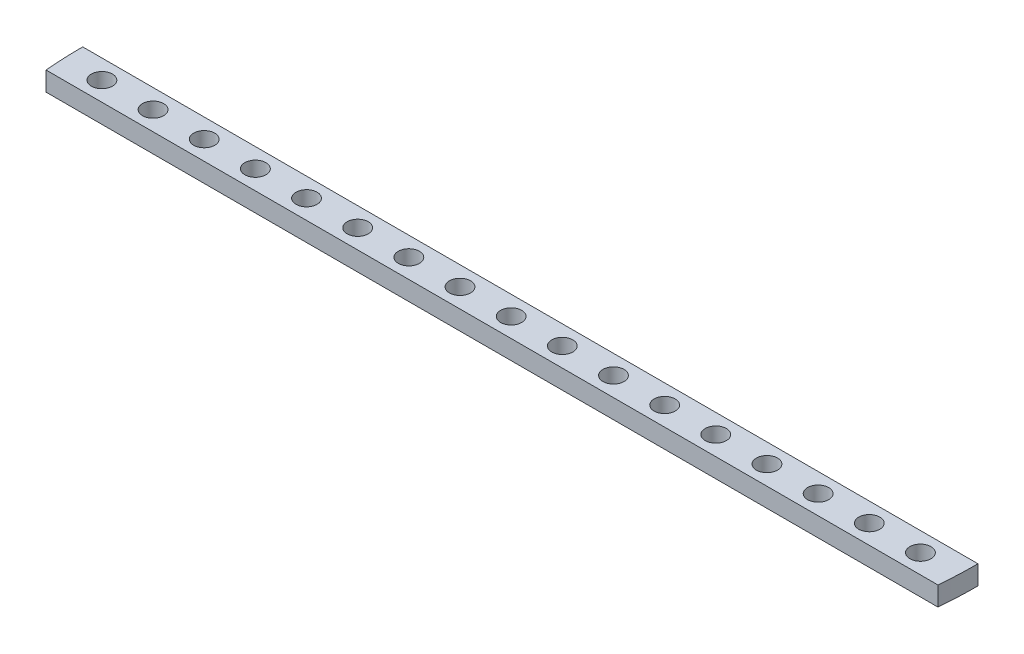
SolidWorks part; units mm, degrees
ref_plane "前视基准面" through (0, 0, 0) normal (0, 0, 1) x (1, 0, 0)
ref_plane "上视基准面" through (0, 0, 0) normal (0, 1, 0) x (1, 0, 0)
ref_plane "右视基准面" through (0, 0, 0) normal (1, 0, 0) x (0, 0, -1)
sketch "草图1" plane through (0, 0, 0) normal (0, 1, 0) x (1, 0, 0)
  line L0 (-50, 0) -> (50, 0)
  arc A0 (50, 0) -> (-50, 0) centre (0, 0) cw
extrude "凸台-拉伸1" add sketch "草图1" along normal blind 4
sketch "草图2" plane through (0, 4, 0) normal (0, 1, 0) x (1, 0, 0)
  line L2 (0, -10.623) -> (10, -10.623)
  line L3 (10, -10.623) -> (10, -30.623)
  line L4 (10, -30.623) -> (-30, -30.623)
  line L5 (-30, -30.623) -> (-30, -10.623)
  line L6 (-30, -10.623) -> (0, -10.623)
extrude "切除-拉伸1" cut sketch "草图2" against normal blind 10
sketch "草图3" plane through (0, 4, 0) normal (0, 1, 0) x (1, 0, 0)
  circle A0 centre (-34.75, -15.623) radius 2.25
  circle A1 centre (-34.75, -25.623) radius 2.25
  circle A2 centre (14.75, -25.623) radius 2.25
  circle A3 centre (14.75, -15.623) radius 2.25
extrude "切除-拉伸2" cut sketch "草图3" against normal blind 10
sketch "草图4" plane through (0, 4, 0) normal (0, 1, 0) x (1, 0, 0)
  circle A0 centre (0, -3) radius 1.65
  circle A1 centre (8, -3) radius 1.65
  circle A2 centre (16, -3) radius 1.65
  circle A3 centre (24, -3) radius 1.65
  circle A4 centre (32, -3) radius 1.65
  circle A5 centre (40, -3) radius 1.65
  circle A6 centre (-40, -3) radius 1.65
  circle A7 centre (-32, -3) radius 1.65
  circle A8 centre (-24, -3) radius 1.65
  circle A9 centre (-16, -3) radius 1.65
  circle A10 centre (-8, -3) radius 1.65
extrude "切除-拉伸3" cut sketch "草图4" against normal blind 10
sketch "草图5" plane through (0, 4, 0) normal (0, 1, 0) x (1, 0, 0)
  line L0 (-70, 0) -> (70, 0)
  circle A0 centre (0, 0) radius 70
  circle A1 centre (0, 0) radius 50
  arc M20 (-50, 0) -> (50, 0) centre (0, 0) ccw
extrude "凸台-拉伸2" add sketch "草图5" against normal blind 4 contours L0 A0 M20
sketch "草图6" plane through (0, 4, 0) normal (0, 1, 0) x (1, 0, 0)
  circle A0 centre (0, -3) radius 1.65
  circle A1 centre (8, -3) radius 1.65
  circle A2 centre (16, -3) radius 1.65
  circle A3 centre (24, -3) radius 1.65
  circle A4 centre (32, -3) radius 1.65
  circle A5 centre (40, -3) radius 1.65
  circle A6 centre (48, -3) radius 1.65
  circle A7 centre (56, -3) radius 1.65
  circle A8 centre (64, -3) radius 1.65
  circle A9 centre (-8, -3) radius 1.65
  circle A10 centre (-16, -3) radius 1.65
  circle A11 centre (-24, -3) radius 1.65
  circle A12 centre (-32, -3) radius 1.65
  circle A13 centre (-40, -3) radius 1.65
  circle A14 centre (-48, -3) radius 1.65
  circle A15 centre (-56, -3) radius 1.65
  circle A16 centre (-64, -3) radius 1.65
  dimension "D1" = 9
  dimension "D2" = 8
extrude "切除-拉伸4" cut sketch "草图6" against normal blind 4
sketch "草图7" plane through (0, 4, 0) normal (0, 1, 0) x (1, 0, 0)
  line L1 (-30, -20.623) -> (-30, -30.623)
  line L2 (10, -20.623) -> (10, -30.623)
  line L3 (-30, -30.623) -> (10, -30.623)
  line L4 (-30, -10.623) -> (-30, -30.623) construction
  line L5 (10, -30.623) -> (10, -10.623) construction
  line L7 (-30, -20.623) -> (10, -20.623)
  line L8 (-30, -20.623) -> (-30, -40.623)
  line L9 (10, -20.623) -> (10, -40.623)
  line L10 (-30, -40.623) -> (10, -40.623)
  line L11 (-34.75, -15.623) -> (14.75, -15.623)
  line L12 (14.75, -15.623) -> (14.75, -25.623)
  line L13 (14.75, -25.623) -> (14.75, -35.623)
  line L14 (-34.75, -15.623) -> (-34.75, -25.623)
  line L15 (-34.75, -25.623) -> (-34.75, -35.623)
  circle A1 centre (-34.75, -35.623) radius 2.25
  circle A2 centre (14.75, -35.623) radius 2.25
extrude "切除-拉伸5" cut sketch "草图7" against normal blind 4
sketch "草图8" plane through (0, 4, 0) normal (0, 1, 0) x (1, 0, 0)
  line L0 (-34.75, -15.623) -> (14.75, -15.623)
  line L1 (14.75, -15.623) -> (14.75, -25.623)
  line L2 (14.75, -25.623) -> (14.75, -20.623)
  line L3 (14.75, -20.623) -> (-41.5549, -20.623)
  line L4 (-41.5549, -20.623) -> (-41.5549, -8.5064)
  line L5 (-41.5549, -8.5064) -> (21.0409, -8.9873)
  line L6 (21.0409, -8.9873) -> (21.0409, -20.623)
  line L7 (21.0409, -20.623) -> (14.75, -20.623)
extrude "凸台-拉伸4" add sketch "草图8" against normal blind 4
sketch "草图9" plane through (0, 4, 0) normal (0, 1, 0) x (1, 0, 0)
  line L0 (0, -70) -> (0, -80)
  line L1 (0, -80) -> (-10, -80)
  line L2 (-10, -80) -> (10, -80)
  line L3 (80, -80) -> (77, -80)
  line L4 (80, -10) -> (80, -150)
  line L5 (-30, -20.623) -> (10, -20.623)
  line L6 (-30, -20.623) -> (-30, -40.623)
  line L7 (10, -20.623) -> (10, -40.623)
  line L8 (-30, -40.623) -> (10, -40.623)
  line L9 (59.377, -90) -> (39.377, -90)
  line L10 (59.377, -50) -> (59.377, -90)
  line L11 (59.377, -50) -> (39.377, -50)
  line L12 (39.377, -50) -> (39.377, -90)
  line L17 (-59.377, -70) -> (-39.377, -70)
  line L18 (-59.377, -110) -> (-59.377, -70)
  line L19 (-59.377, -110) -> (-39.377, -110)
  line L20 (-39.377, -110) -> (-39.377, -70)
  line L21 (-80, -10) -> (-80, -150)
  arc A1 (80, -10) -> (80, -150) centre (80, -80) ccw
  circle A2 centre (77, -80) radius 1.65
  circle A3 centre (77, -72) radius 1.65
  circle A4 centre (77, -64) radius 1.65
  circle A5 centre (77, -56) radius 1.65
  circle A6 centre (77, -48) radius 1.65
  circle A7 centre (77, -40) radius 1.65
  circle A8 centre (77, -32) radius 1.65
  circle A9 centre (77, -24) radius 1.65
  circle A10 centre (77, -16) radius 1.65
  circle A11 centre (77, -88) radius 1.65
  circle A12 centre (77, -96) radius 1.65
  circle A13 centre (77, -104) radius 1.65
  circle A14 centre (77, -112) radius 1.65
  circle A15 centre (77, -120) radius 1.65
  circle A16 centre (77, -128) radius 1.65
  circle A17 centre (77, -136) radius 1.65
  circle A18 centre (77, -144) radius 1.65
  circle A19 centre (14.75, -25.623) radius 2.25
  circle A20 centre (14.75, -35.623) radius 2.25
  circle A21 centre (-34.75, -25.623) radius 2.25
  circle A22 centre (-34.75, -35.623) radius 2.25
  circle A23 centre (44.377, -45.25) radius 2.25
  circle A24 centre (54.377, -45.25) radius 2.25
  circle A25 centre (54.377, -94.75) radius 2.25
  circle A26 centre (44.377, -94.75) radius 2.25
  circle A31 centre (-44.377, -114.75) radius 2.25
  circle A32 centre (-54.377, -114.75) radius 2.25
  circle A33 centre (-54.377, -65.25) radius 2.25
  circle A34 centre (-44.377, -65.25) radius 2.25
  circle A35 centre (-77, -144) radius 1.65
  circle A36 centre (-77, -136) radius 1.65
  circle A37 centre (-77, -128) radius 1.65
  circle A38 centre (-77, -120) radius 1.65
  circle A39 centre (-77, -112) radius 1.65
  circle A40 centre (-77, -104) radius 1.65
  circle A41 centre (-77, -96) radius 1.65
  circle A42 centre (-77, -88) radius 1.65
  circle A43 centre (-77, -80) radius 1.65
  circle A44 centre (-77, -72) radius 1.65
  circle A45 centre (-77, -64) radius 1.65
  circle A46 centre (-77, -56) radius 1.65
  circle A47 centre (-77, -48) radius 1.65
  circle A48 centre (-77, -40) radius 1.65
  circle A49 centre (-77, -32) radius 1.65
  circle A50 centre (-77, -24) radius 1.65
  circle A51 centre (-77, -16) radius 1.65
  arc A52 (-80, -10) -> (-80, -150) centre (-80, -80) cw
  point P100 (0, -80)
extrude "凸台-拉伸7" add sketch "草图9" against normal blind 4
sketch "草图10" plane through (0, 4, 0) normal (0, 1, 0) x (1, 0, 0)
  line L0 (59.377, -50) -> (59.377, -90)
  line L1 (59.377, -50) -> (39.377, -50)
  line L2 (59.377, -90) -> (39.377, -90)
  line L3 (39.377, -50) -> (39.377, -90)
  circle A0 centre (54.377, -45.25) radius 2.25
  circle A1 centre (44.377, -45.25) radius 2.25
extrude "切除-拉伸6" cut sketch "草图10" against normal blind 4
sketch "草图11" plane through (0, 0, 0) normal (0, -1, 0) x (1, 0, 0)
  line L0 (0, 0) -> (0, 6)
  line L1 (0, 6) -> (-85.0456, 6)
  line L2 (-85.0456, 6) -> (-85.0456, 166.3409)
  line L3 (-85.0456, 166.3409) -> (96.12, 166.3409)
  line L4 (96.12, 166.3409) -> (96.12, 6)
  line L5 (96.12, 6) -> (0, 6)
  circle A0 centre (0, 0) radius 70
extrude "切除-拉伸7" cut sketch "草图11" against normal blind 4 contours A0 L5 L4 L3 L2 L1 | L5 A0 L1
sketch "草图12" plane through (0, 0, 0) normal (0, 0, -1) x (-1, 0, 0)
  line L0 (-70, 4) -> (70, 4)
  line L1 (-70, 4) -> (-70, 3)
  line L2 (70, 4) -> (70, 3)
  line L3 (-70, 3) -> (70, 3)
extrude "切除-拉伸8" cut sketch "草图12" against normal blind 10
